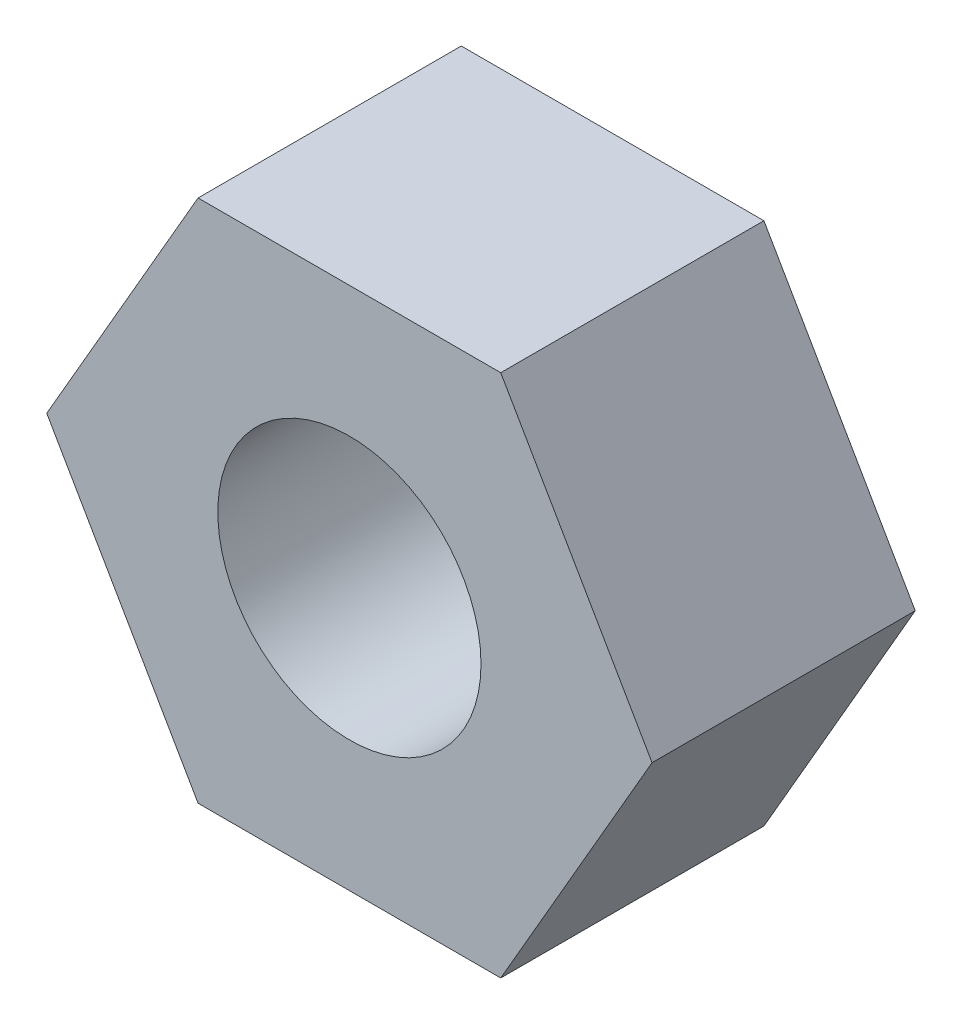
SolidWorks part; units mm, degrees
ref_plane "Front Plane" through (0, 0, 0) normal (0, 0, 1) x (1, 0, 0)
ref_plane "Top Plane" through (0, 0, 0) normal (0, 1, 0) x (1, 0, 0)
ref_plane "Right Plane" through (0, 0, 0) normal (1, 0, 0) x (0, 0, -1)
sketch "Sketch1" plane through (0, 0, 0) normal (0, 0, 1) x (1, 0, 0)
  line L1 (5.75, 9.9593) -> (-5.75, 9.9593)
  line L2 (-5.75, 9.9593) -> (-11.5, 0)
  line L3 (-11.5, 0) -> (-5.75, -9.9593)
  line L4 (-5.75, -9.9593) -> (5.75, -9.9593)
  line L5 (5.75, -9.9593) -> (11.5, 0)
  line L6 (11.5, 0) -> (5.75, 9.9593)
  circle A0 centre (0, 0) radius 9.9593 construction
  dimension "D1" = 11.5
extrude "Boss-Extrude1" add sketch "Sketch1" along normal blind 10
sketch "Sketch2" plane through (0, 0, 10) normal (0, 0, 1) x (1, 0, 0)
  circle A0 centre (0, 0) radius 5
  dimension "D1" = 10
extrude "Cut-Extrude1" cut sketch "Sketch2" against normal blind 10
